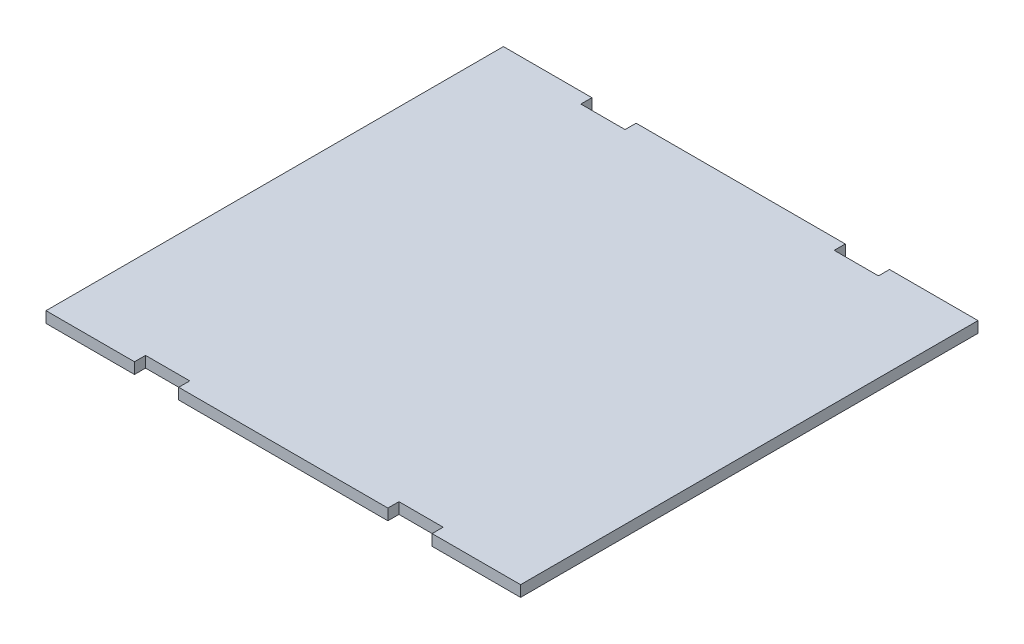
SolidWorks part; units mm, degrees
ref_plane "Front Plane" through (0, 0, 0) normal (0, 0, 1) x (1, 0, 0)
ref_plane "Top Plane" through (0, 0, 0) normal (0, 1, 0) x (1, 0, 0)
ref_plane "Right Plane" through (0, 0, 0) normal (1, 0, 0) x (0, 0, -1)
sketch "Sketch1" plane through (0, 0, 0) normal (0, 1, 0) x (1, 0, 0)
  line L0 (-68.1228, 62.484) -> (68.1228, 62.484) construction
  line L1 (-68.1228, 65.659) -> (-42.7228, 65.659)
  line L2 (-68.1228, 65.659) -> (-68.1228, -65.659)
  line L3 (-68.1228, -65.659) -> (-42.7228, -65.659)
  line L4 (68.1228, 65.659) -> (68.1228, -65.659)
  line L5 (-68.1228, -62.484) -> (68.1228, -62.484) construction
  line L6 (-42.7228, 65.659) -> (-42.7228, 62.484)
  line L7 (-42.7228, 62.484) -> (-30.0228, 62.484)
  line L8 (-30.0228, 62.484) -> (-30.0228, 65.659)
  line L9 (-42.7228, -65.659) -> (-42.7228, -62.484)
  line L10 (-42.7228, -62.484) -> (-30.0228, -62.484)
  line L11 (-30.0228, -62.484) -> (-30.0228, -65.659)
  line L12 (30.0228, 65.659) -> (30.0228, 62.484)
  line L13 (30.0228, 62.484) -> (42.7228, 62.484)
  line L14 (42.7228, 62.484) -> (42.7228, 65.659)
  line L15 (30.0228, -65.659) -> (30.0228, -62.484)
  line L16 (30.0228, -62.484) -> (42.7228, -62.484)
  line L17 (42.7228, -62.484) -> (42.7228, -65.659)
  line L18 (-30.0228, 65.659) -> (30.0228, 65.659)
  line L19 (42.7228, 65.659) -> (68.1228, 65.659)
  line L20 (-30.0228, -65.659) -> (30.0228, -65.659)
  line L21 (42.7228, -65.659) -> (68.1228, -65.659)
  point P6 (-68.1228, 0)
  dimension "D1" = 136.2456
  dimension "D2" = 131.318
  dimension "D3" = 3.175
  dimension "D4" = 3.175
  dimension "D5" = 12.7
  dimension "D6" = 12.7
  dimension "D7" = 25.4
  dimension "D8" = 25.4
  dimension "D9" = 12.7
  dimension "D10" = 25.4
  dimension "D11" = 12.7
  dimension "D12" = 25.4
extrude "Boss-Extrude1" add sketch "Sketch1" along normal blind 3.175
